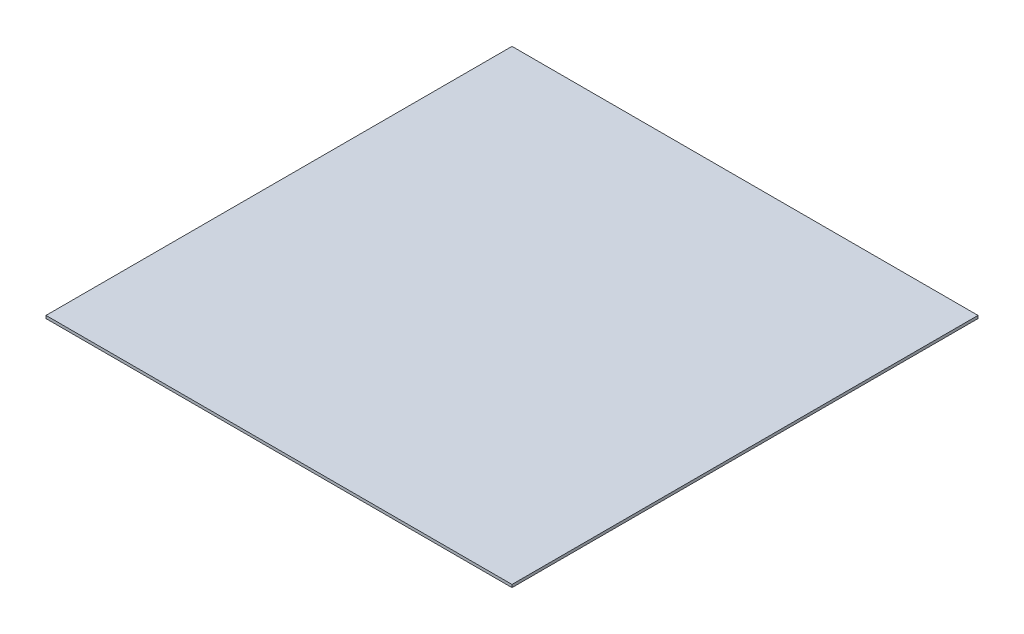
SolidWorks part; units mm, degrees
ref_plane "Front Plane" through (0, 0, 0) normal (0, 0, 1) x (1, 0, 0)
ref_plane "Top Plane" through (0, 0, 0) normal (0, 1, 0) x (1, 0, 0)
ref_plane "Right Plane" through (0, 0, 0) normal (1, 0, 0) x (0, 0, -1)
sketch "Sketch1" plane through (0, 0, 0) normal (0, 1, 0) x (1, 0, 0)
  line L1 (0, 0) -> (500, 0)
  line L2 (0, 0) -> (0, -500)
  line L3 (0, -500) -> (500, -500)
  line L4 (500, 0) -> (500, -500)
extrude "Boss-Extrude1" add sketch "Sketch1" along normal blind 2.9972
